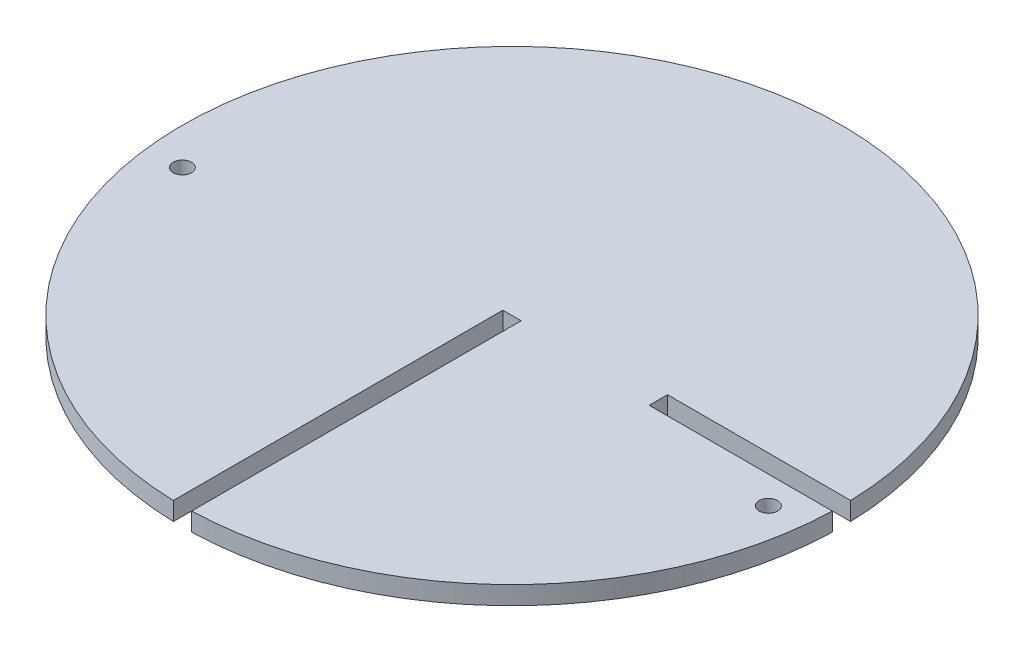
SolidWorks part; units mm, degrees
ref_plane "Front Plane" through (0, 0, 0) normal (0, 0, 1) x (1, 0, 0)
ref_plane "Top Plane" through (0, 0, 0) normal (0, 1, 0) x (1, 0, 0)
ref_plane "Right Plane" through (0, 0, 0) normal (1, 0, 0) x (0, 0, -1)
sketch "Sketch1" plane through (0, 0, 0) normal (0, 1, 0) x (1, 0, 0)
  circle A0 centre (0, 0) radius 114.3
  dimension "D1" = 228.6
extrude "Boss-Extrude1" add sketch "Sketch1" along normal blind 6.35
sketch "Sketch2" plane through (0, 6.35, 0) normal (0, 1, 0) x (1, 0, 0)
  line L0 (0, 0) -> (0, -114.3) construction
  line L2 (-3.175, -114.3) -> (3.175, -114.3)
  line L3 (-3.175, -114.3) -> (-3.175, 0)
  line L4 (-3.175, 0) -> (3.175, 0)
  line L5 (3.175, -114.3) -> (3.175, 0)
  line L6 (-3.175, -114.3) -> (3.175, 0) construction
  line L7 (-3.175, 0) -> (3.175, -114.3) construction
  circle A0 centre (0, 0) radius 114.3 construction
  point P5 (0, -57.15)
  dimension "D1" = 6.35
extrude "Cut-Extrude1" cut sketch "Sketch2" against normal blind 6.35
sketch "Sketch3" plane through (0, 6.35, 0) normal (0, 1, 0) x (1, 0, 0)
  line L0 (0, 0) -> (50000, 0) construction
  line L1 (114.2559, 3.175) -> (120.6059, 3.175)
  line L2 (50.7559, -3.175) -> (114.2559, -3.175)
  line L3 (50.7559, -3.175) -> (50.7559, 3.175)
  line L4 (50.7559, 3.175) -> (114.2559, 3.175)
  line L5 (114.2559, -3.175) -> (114.2559, 3.175) construction
  line L6 (50.7559, -3.175) -> (114.2559, 3.175) construction
  line L7 (50.7559, 3.175) -> (114.2559, -3.175) construction
  line L8 (120.6059, 3.175) -> (120.6059, -3.175)
  line L9 (120.6059, -3.175) -> (114.2559, -3.175)
  arc A0 (3.175, -114.2559) -> (-3.175, -114.2559) centre (0, 0) ccw construction
  point P3 (82.5059, 0)
  dimension "D1" = 6.35
  dimension "D2" = 63.5
  dimension "D3" = 6.35
extrude "Cut-Extrude2" cut sketch "Sketch3" against normal through all contours L2 L9 L8 L1 L4 L3
sketch "Sketch4" plane through (0, 6.35, 0) normal (0, 1, 0) x (1, 0, 0)
  line L0 (0, 0) -> (0, -50000) construction
  line L1 (3.175, 0) -> (-3.175, 0) construction
  line L2 (-2.1046, -12.7) -> (49997.8954, -12.7) construction
  circle A0 centre (101.6, -12.7) radius 3.175
  circle A1 centre (-101.6, -12.7) radius 3.175
  point P4 (0, 0)
  dimension "D4" = 6.35
  dimension "D5" = 6.35
  dimension "D1" = 101.6
  dimension "D2" = 101.6
  dimension "D3" = 12.7
extrude "Cut-Extrude3" cut sketch "Sketch4" against normal through all
